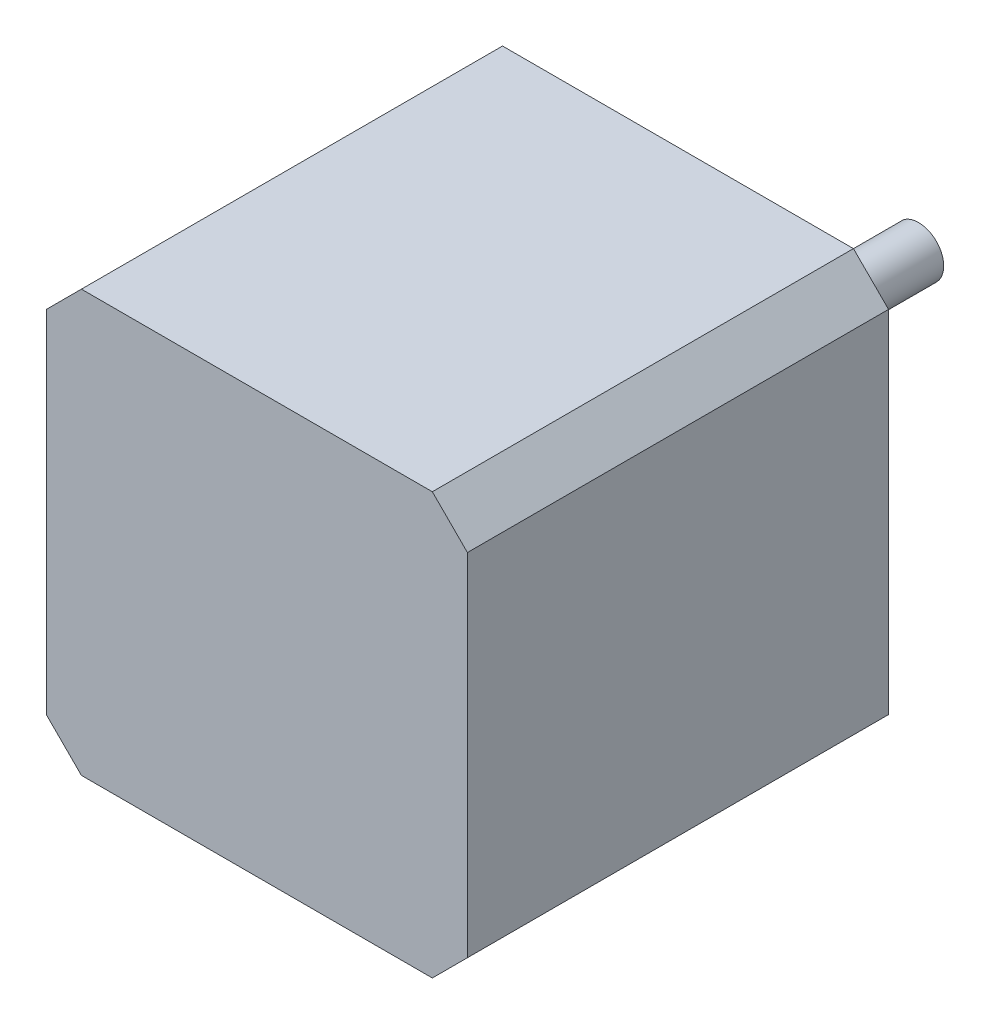
SolidWorks part; units mm, degrees
ref_plane "Alzado" through (0, 0, 0) normal (0, 0, 1) x (1, 0, 0)
ref_plane "Planta" through (0, 0, 0) normal (0, 1, 0) x (1, 0, 0)
ref_plane "Vista lateral" through (0, 0, 0) normal (1, 0, 0) x (0, 0, -1)
sketch "Croquis1" plane through (0, 0, 0) normal (0, 0, 1) x (1, 0, 0)
  line L1 (-17.5, -21) -> (17.5, -21)
  line L2 (-21, -17.5) -> (-21, 17.5)
  line L3 (-17.5, 21) -> (17.5, 21)
  line L4 (21, -17.5) -> (21, 17.5)
  line L5 (-19.25, -19.25) -> (19.25, 19.25) construction
  line L6 (-19.25, 19.25) -> (19.25, -19.25) construction
  line L16 (-17.5, 21) -> (-21, 17.5)
  line L17 (-21, -17.5) -> (-17.5, -21)
  line L18 (17.5, 21) -> (21, 17.5)
  line L19 (17.5, -21) -> (21, -17.5)
  point P0 (0, 0)
extrude "Saliente-Extruir1" add sketch "Croquis1" along normal blind 42 contours L1 L19 L4 L18 L3 L16 L2 L17
sketch "Croquis2" plane through (0, 0, 0) normal (0, 0, -1) x (-1, 0, 0)
  circle A0 centre (0, 0) radius 11
  circle A1 centre (0, 0) radius 5
  dimension "D1" = 22
  dimension "D2" = 10
extrude "Saliente-Extruir3" add sketch "Croquis2" along normal blind 3 contours A0 | A1
sketch "Croquis3" plane through (0, 0, 0) normal (0, 0, -1) x (-1, 0, 0)
  line L0 (-2.5, 0) -> (1.5, 0)
  line L1 (1.5, 0) -> (1.5, 2)
  line L2 (1.5, 0) -> (1.5, -2)
  line L3 (1.5, -2) -> (1.5, 0)
  circle A0 centre (0, 0) radius 2.5
  dimension "D1" = 5
  dimension "D2" = 4
extrude "Saliente-Extruir4" add sketch "Croquis3" along normal blind 24 contours L0 A0 L2 | L1 A0 L0
sketch "Croquis7" plane through (0, 0, 0) normal (0, 0, -1) x (-1, 0, 0)
  line L0 (0, 0) -> (-15.9099, 15.9099)
  line L1 (0, 0) -> (-15.9099, -15.9099)
  line L2 (0, 0) -> (15.9099, -15.9099)
  line L3 (0, 0) -> (15.9099, 15.9099)
  circle A0 centre (-15.9099, 15.9099) radius 1.25
  circle A1 centre (-15.9099, -15.9099) radius 1.25
  circle A2 centre (15.9099, -15.9099) radius 1.25
  circle A3 centre (15.9099, 15.9099) radius 1.25
  dimension "D2" = 2.5
  dimension "D4" = 2.5
  dimension "D6" = 2.5
  dimension "D8" = 2.5
  dimension "D1" = 22.5
  dimension "D3" = 22.5
  dimension "D5" = 22.5
  dimension "D7" = 22.5
extrude "Cortar-Extruir2" cut sketch "Croquis7" against normal blind 15
